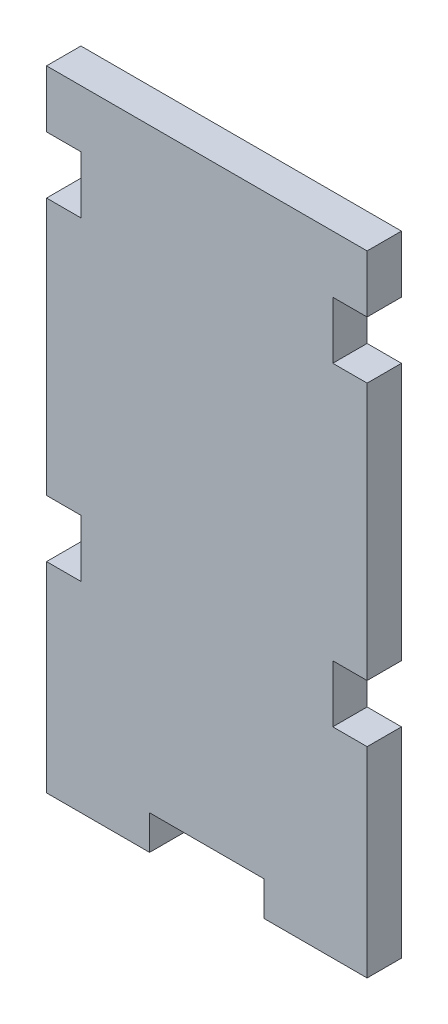
SolidWorks part; units mm, degrees
ref_plane "Plan de face" through (0, 0, 0) normal (0, 0, 1) x (1, 0, 0)
ref_plane "Plan de dessus" through (0, 0, 0) normal (0, 1, 0) x (1, 0, 0)
ref_plane "Plan de droite" through (0, 0, 0) normal (1, 0, 0) x (0, 0, -1)
sketch "Esquisse1" plane through (0, 0, 0) normal (0, 0, 1) x (1, 0, 0)
  line L1 (0, 0) -> (44, 0)
  line L2 (0, 0) -> (0, 110)
  line L3 (0, 110) -> (44, 110)
  line L4 (44, 0) -> (44, 110)
  dimension "D1" = 44
  dimension "D2" = 110
extrude "Boss.-Extru.1" add sketch "Esquisse1" along normal blind 6
sketch "Esquisse4" plane through (0, 0, 6) normal (0, 0, 1) x (1, 0, 0)
  line L0 (0, 110) -> (0, 0) construction
  line L1 (0, 110) -> (-6, 110)
  line L2 (0, 110) -> (0, 100)
  line L3 (0, 100) -> (-6, 100)
  line L4 (-6, 110) -> (-6, 100)
  line L5 (0, 90) -> (-6, 90)
  line L6 (0, 90) -> (0, 45)
  line L7 (0, 45) -> (-6, 45)
  line L8 (-6, 90) -> (-6, 45)
  line L9 (44, 0) -> (44, 110) construction
  line L10 (0, 0) -> (-6, 0)
  line L11 (0, 0) -> (0, 35)
  line L12 (0, 35) -> (-6, 35)
  line L13 (-6, 0) -> (-6, 35)
  line L14 (44, 0) -> (50, 0)
  line L15 (44, 0) -> (44, 35)
  line L16 (44, 35) -> (50, 35)
  line L17 (50, 0) -> (50, 35)
  line L18 (44, 45) -> (50, 45)
  line L19 (44, 45) -> (44, 90)
  line L20 (44, 90) -> (50, 90)
  line L21 (50, 45) -> (50, 90)
  line L23 (44, 110) -> (50, 110)
  line L24 (44, 110) -> (44, 100)
  line L25 (44, 100) -> (50, 100)
  line L26 (50, 110) -> (50, 100)
  dimension "D1" = 6
  dimension "D2" = 6
  dimension "D3" = 6
  dimension "D4" = 6
  dimension "D5" = 6
  dimension "D6" = 6
  dimension "D7" = 10
  dimension "D8" = 10
  dimension "D9" = 45
  dimension "D10" = 10
  dimension "D11" = 10
  dimension "D12" = 45
  dimension "D13" = 10
  dimension "D14" = 10
extrude "Boss.-Extru.2" add sketch "Esquisse4" against normal blind 6
sketch "Esquisse5" plane through (0, 0, 0) normal (0, 0, -1) x (-1, 0, 0)
  line L0 (6, 0) -> (-50, 0) construction
  line L1 (-32, 0) -> (-12, 0)
  line L2 (-32, 0) -> (-32, 6)
  line L3 (-32, 6) -> (-12, 6)
  line L4 (-12, 0) -> (-12, 6)
  line L5 (-44, 35) -> (-44, 45) construction
  line L6 (0, 45) -> (0, 35) construction
  dimension "D1" = 6
  dimension "D2" = 12
  dimension "D3" = 12
extrude "Enlèv. mat.-Extru.1" cut sketch "Esquisse5" against normal blind 6
